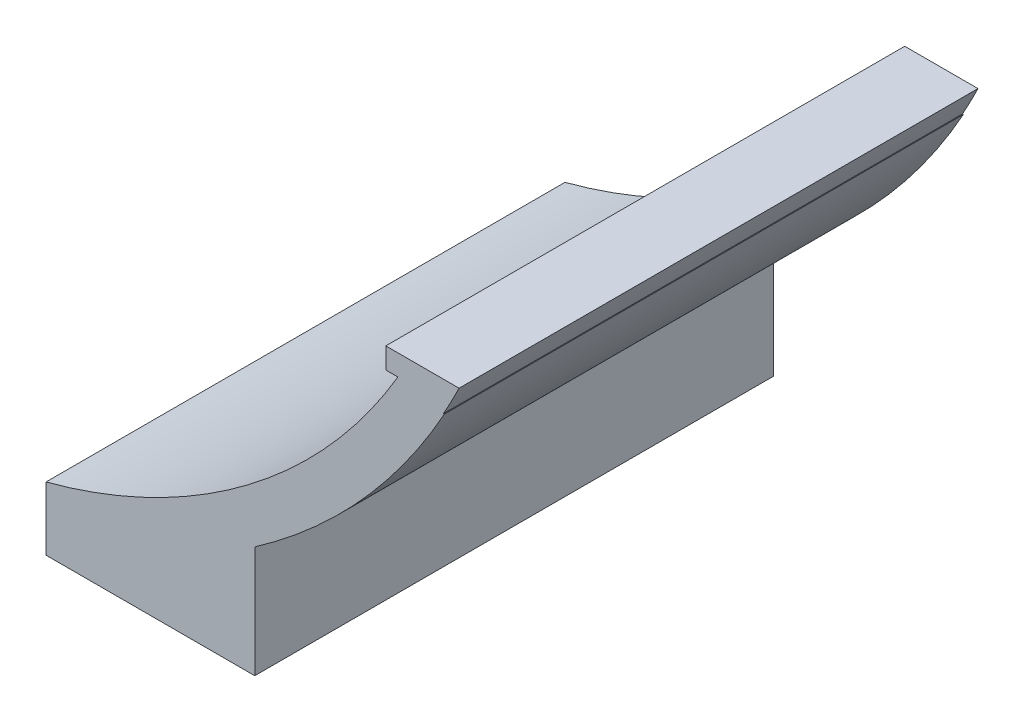
SolidWorks part; units mm, degrees
ref_plane "前视基准面" through (0, 0, 0) normal (0, 0, 1) x (1, 0, 0)
ref_plane "上视基准面" through (0, 0, 0) normal (0, 1, 0) x (1, 0, 0)
ref_plane "右视基准面" through (0, 0, 0) normal (1, 0, 0) x (0, 0, -1)
sketch "草图1" plane through (0, 0, 0) normal (0, 0, 1) x (1, 0, 0)
  arc A0 (-203, 0) -> (203, 0) centre (0, 0) ccw
  arc A1 (-210, 0) -> (210, 0) centre (0, 0) ccw
  arc A2 (-203, 0) -> (203, 0) centre (0, 0) ccw
  circle A3 centre (0, 0) radius 210
  circle A4 centre (0, 0) radius 203
  point P12 (0, 0)
extrude "凸台-拉伸2" add sketch "草图1" along normal blind 174
sketch "草图2" plane through (0, 0, 174) normal (0, 0, 1) x (1, 0, 0)
  line L0 (-173.7354, -102) -> (-170.7354, -102)
  line L1 (-170.7354, -102) -> (-170.7354, -105)
  line L2 (-170.7354, -105) -> (-173.7354, -105)
  line L3 (173.7354, -102) -> (170.7354, -102)
  line L4 (-173.7354, -102) -> (-175.5135, -102)
  line L6 (173.7354, -102) -> (175.5135, -102)
  line L7 (173.7354, -105) -> (170.7354, -105)
  line L8 (170.7354, -105) -> (170.7354, -102)
  circle A0 centre (0, 0) radius 203 construction
  arc A1 (0, -203) -> (-173.7354, -105) centre (0, 0) ccw
  circle M4 centre (0, 0) radius 203
extrude "凸台-拉伸4" add sketch "草图2" against normal up to surface (174 mm away) contours L0 L4 L2 L1 M4 | L8 L7 L6 L3 M4 up to face at (203, 0, 0)
sketch "草图3" plane through (0, 0, 174) normal (0, 0, 1) x (1, 0, 0)
  line L0 (-170.7354, -102) -> (238.3336, -102)
  line L1 (238.3336, -102) -> (254.3342, 272.2925)
  line L2 (254.3342, 272.2925) -> (-334.5694, 221.8511)
  line L3 (-170.7354, -102) -> (-306.8306, -102)
  line L4 (-306.8306, -102) -> (-334.5694, 221.8511)
extrude "切除-拉伸1" cut sketch "草图3" against normal blind 654
ref_plane "基准面1" through (0, -209.75, 0) normal (0, 1, 0) x (1, 0, 0)
sketch "草图5" plane through (0, 0, 174) normal (0, 0, 1) x (1, 0, 0)
  line L0 (0, -209.75) -> (120, -209.75)
  line L1 (95.7, -209.75) -> (-95.7, -209.75) construction
  line L2 (120, -209.75) -> (120, -172.0322)
  line L3 (0, -209.75) -> (-120, -209.75)
  line L4 (-120, -209.75) -> (-120, -172.0322)
  arc A0 (-120, -172.0322) -> (120, -172.0322) centre (0, 0) ccw
  arc M3 (-183.5647, -102) -> (183.5647, -102) centre (0, 0) ccw
extrude "凸台-拉伸5" add sketch "草图5" against normal up to surface (174 mm away) contours L4 L3 M3 | L0 L2 M3 up to face at (0, -129.25, 0)
sketch "草图6" plane through (0, 0, 174) normal (0, 0, 1) x (1, 0, 0)
  line L0 (-175.5135, -102) -> (-166.1957, -102)
  line L1 (175.5135, -102) -> (166.1957, -102)
  arc A0 (-166.1957, -102) -> (166.1957, -102) centre (0, 0) ccw
  arc A1 (-175.5135, -102) -> (175.5135, -102) centre (0, 0) ccw
extrude "凸台-拉伸6" add sketch "草图6" against normal up to surface (174 mm away) up to face at (0, -151.228, 0)
sketch "草图7" plane through (0, 0, 174) normal (0, 0, 1) x (1, 0, 0)
  line L0 (-166.9331, -92) -> (-166.9331, -95)
  line L1 (171.9331, -92) -> (166.9331, -92)
  line L2 (-171.9331, -92) -> (-166.9331, -92)
  line L3 (-188.4969, -92) -> (-171.9331, -92)
  line L4 (171.9331, -92) -> (188.4969, -92)
  line L5 (-166.9331, -95) -> (-170.2939, -95)
  line L6 (166.9331, -92) -> (166.9331, -95)
  line L7 (166.9331, -95) -> (170.2939, -95)
  arc A1 (-188.4969, -92) -> (188.4969, -92) centre (0, 0) ccw
  arc A2 (-170.2939, -95) -> (170.2939, -95) centre (0, 0) ccw
extrude "凸台-拉伸7" add sketch "草图7" against normal up to surface (174 mm away) up to face at (0, -169.2192, 0)
sketch "草图8" plane through (0, 0, 0) normal (0, 0, -1) x (-1, 0, 0)
  line L0 (166.9331, -92) -> (163.9331, -92)
  line L1 (163.9331, -92) -> (163.9331, -99)
  line L2 (163.9331, -99) -> (168, -99)
  line L3 (166.9331, -92) -> (166.9331, -95)
  line L4 (166.9331, -95) -> (170.2939, -95)
  line L6 (-166.9331, -95) -> (-170.2939, -95)
  line L7 (-166.9331, -92) -> (-166.9331, -95)
  line L8 (-163.9331, -99) -> (-168, -99)
  line L9 (-163.9331, -92) -> (-163.9331, -99)
  line L10 (-166.9331, -92) -> (-163.9331, -92)
  arc A0 (-170.2939, -95) -> (170.2939, -95) centre (0, 0) ccw construction
  arc A1 (168, -99) -> (170.2939, -95) centre (0, 0) ccw
  arc A2 (-168, -99) -> (-170.2939, -95) centre (0, 0) cw
extrude "凸台-拉伸8" add sketch "草图8" against normal up to surface (174 mm away) up to face at (0, -135.959, 174)
sketch "草图9" plane through (0, 0, 174) normal (0, 0, 1) x (1, 0, 0)
  line L0 (0, 0) -> (0, -337.2155)
  line L3 (-50, -195) -> (-50, -209.75)
  line L4 (-10.2439, -209.75) -> (-120, -209.75) construction
  line L5 (-50, -209.75) -> (50, -209.75)
  line L6 (10.2439, -209.75) -> (120, -209.75) construction
  line L7 (50, -209.75) -> (50, -195)
  line L8 (-50, -195) -> (-50, -182.2253)
  line L9 (-50, -182.2253) -> (50, -182.2253)
  line L10 (50, -182.2253) -> (50, -195)
  arc M4 (168, -99) -> (-168, -99) centre (0, 0) cw
  line M12 (-120, -209.75) -> (-10.2439, -209.75)
  line M14 (10.2439, -209.75) -> (120, -209.75)
extrude "切除-拉伸2" cut sketch "草图9" against normal blind 654 contours L9 L8 L0 M4 | L8 L3 L5 L0 M12 M4 | L10 L0 L5 L7 M4 M14 | L10 L9 L0 M4
sketch "草图10" plane through (0, -209.75, 0) normal (0, 1, 0) x (1, 0, 0)
  line L1 (-10.2439, 0) -> (10.2439, 0)
  line L2 (-10.2439, 0) -> (-10.2439, -174)
  line L3 (-10.2439, -174) -> (10.2439, -174)
  line L4 (10.2439, 0) -> (10.2439, -174)
extrude "切除-拉伸3" cut sketch "草图10" against normal mid plane 654
sketch "草图11" plane through (0, 0, 0) normal (0, 0, -1) x (-1, 0, 0)
  line L1 (18.7676, -16.6345) -> (254.4053, -16.6345)
  line L2 (18.7676, -16.6345) -> (18.7676, -265.8266)
  line L3 (18.7676, -265.8266) -> (254.4053, -265.8266)
  line L4 (254.4053, -16.6345) -> (254.4053, -265.8266)
extrude "切除-拉伸4" cut sketch "草图11" against normal blind 238
